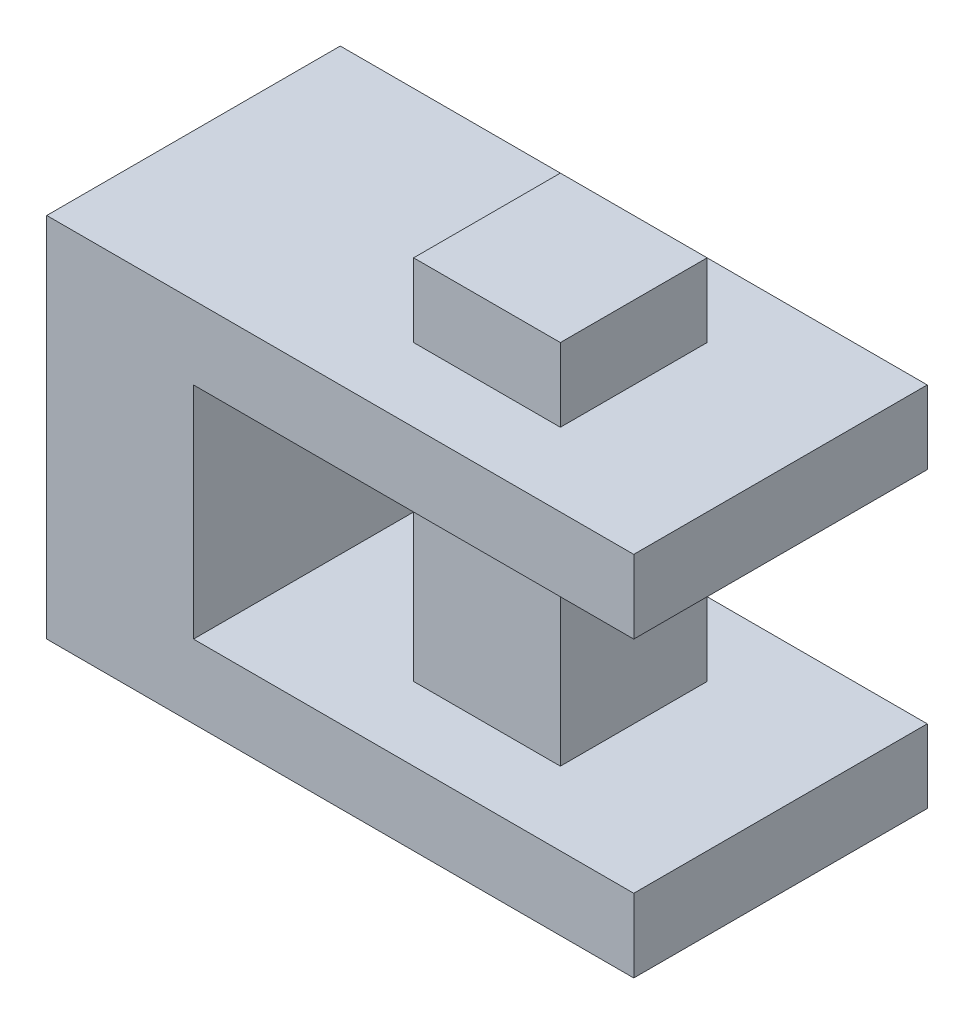
SolidWorks part; units mm, degrees
ref_plane "Front Plane" through (0, 0, 0) normal (0, 0, 1) x (1, 0, 0)
ref_plane "Top Plane" through (0, 0, 0) normal (0, 1, 0) x (1, 0, 0)
ref_plane "Right Plane" through (0, 0, 0) normal (1, 0, 0) x (0, 0, -1)
sketch "Sketch1" plane through (0, 0, 0) normal (0, 0, 1) x (1, 0, 0)
  line L0 (0, 0) -> (40, 0)
  line L1 (40, 0) -> (40, 5)
  line L2 (40, 5) -> (10, 5)
  line L3 (10, 5) -> (10, 20)
  line L4 (10, 20) -> (40, 20)
  line L5 (40, 20) -> (40, 25)
  line L6 (40, 25) -> (0, 25)
  line L7 (0, 25) -> (0, 0)
extrude "Boss-Extrude1" add sketch "Sketch1" along normal blind 20
sketch "Sketch2" plane through (0, 25, 0) normal (0, 1, 0) x (1, 0, 0)
  line L1 (20, -15) -> (30, -15)
  line L2 (20, -15) -> (20, -5)
  line L3 (20, -5) -> (30, -5)
  line L4 (30, -15) -> (30, -5)
extrude "Boss-Extrude2" add sketch "Sketch2" along normal blind 5 and the other way through all
